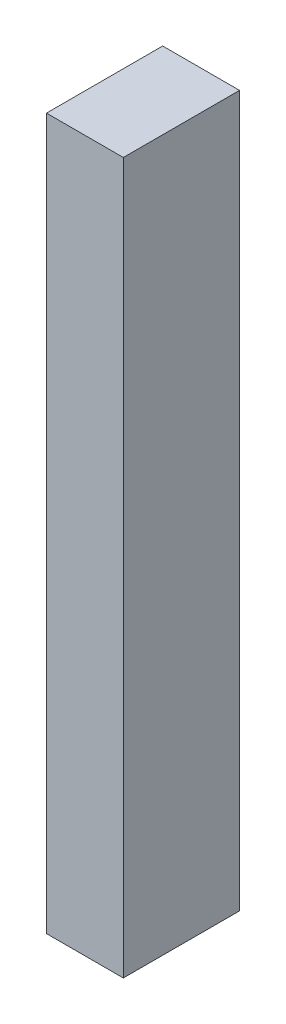
SolidWorks part; units mm, degrees
ref_plane "Front Plane" through (0, 0, 0) normal (0, 0, 1) x (1, 0, 0)
ref_plane "Top Plane" through (0, 0, 0) normal (0, 1, 0) x (1, 0, 0)
ref_plane "Right Plane" through (0, 0, 0) normal (1, 0, 0) x (0, 0, -1)
other "Configuration Table"
sketch "Sketch3" plane through (0, 0, 0) normal (0, 0, 1) x (1, 0, 0)
  line L1 (10, -4.1314) -> (10.6613, -4.1314)
  line L2 (10, -4.1314) -> (10, 1.9831)
  line L3 (10, 1.9831) -> (10.6613, 1.9831)
  line L4 (10.6613, -4.1314) -> (10.6613, 1.9831)
extrude "Extrude1" add sketch "Sketch3" along normal blind 1
